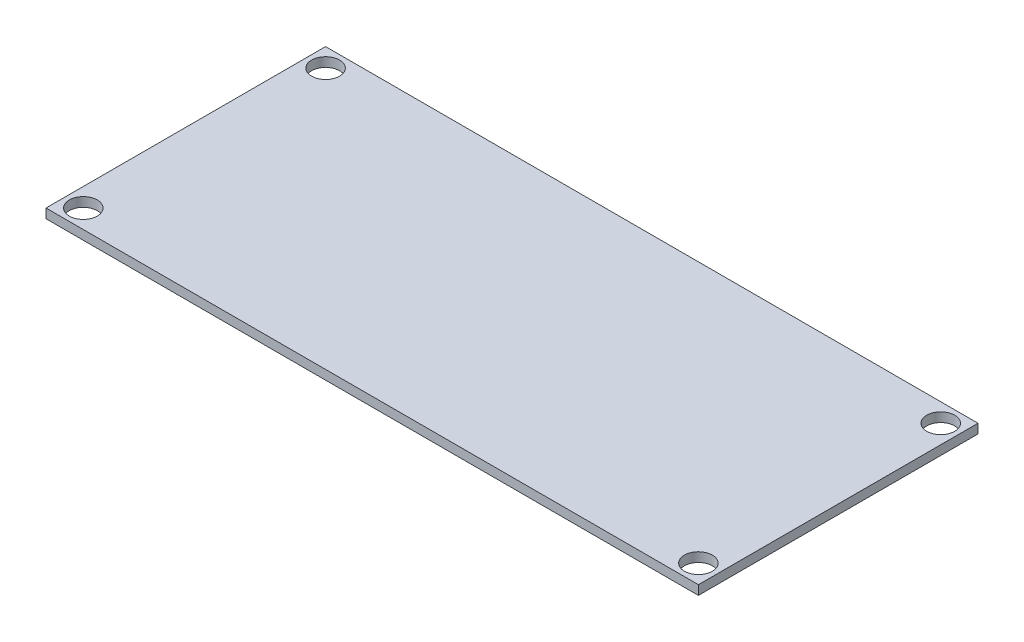
SolidWorks part; units mm, degrees
ref_plane "Front Plane" through (0, 0, 0) normal (0, 0, 1) x (1, 0, 0)
ref_plane "Top Plane" through (0, 0, 0) normal (0, 1, 0) x (1, 0, 0)
ref_plane "Right Plane" through (0, 0, 0) normal (1, 0, 0) x (0, 0, -1)
sketch "Sketch1" plane through (0, 0, 0) normal (0, 1, 0) x (1, 0, 0)
  line L1 (-35, -15) -> (35, -15)
  line L2 (-35, -15) -> (-35, 15)
  line L3 (-35, 15) -> (35, 15)
  line L4 (35, -15) -> (35, 15)
  line L5 (-35, -15) -> (35, 15) construction
  line L6 (-35, 15) -> (35, -15) construction
  circle A0 centre (-33, 13) radius 1.5
  circle A1 centre (33, 13) radius 1.5
  circle A2 centre (33, -13) radius 1.5
  circle A3 centre (-33, -13) radius 1.5
  point P0 (0, 0)
  dimension "D3" = 3
  dimension "D1" = 70
  dimension "D2" = 30
  dimension "D4" = 2
  dimension "D5" = 2
  dimension "D6" = 2
  dimension "D7" = 2
extrude "Boss-Extrude1" add sketch "Sketch1" along normal blind 1
